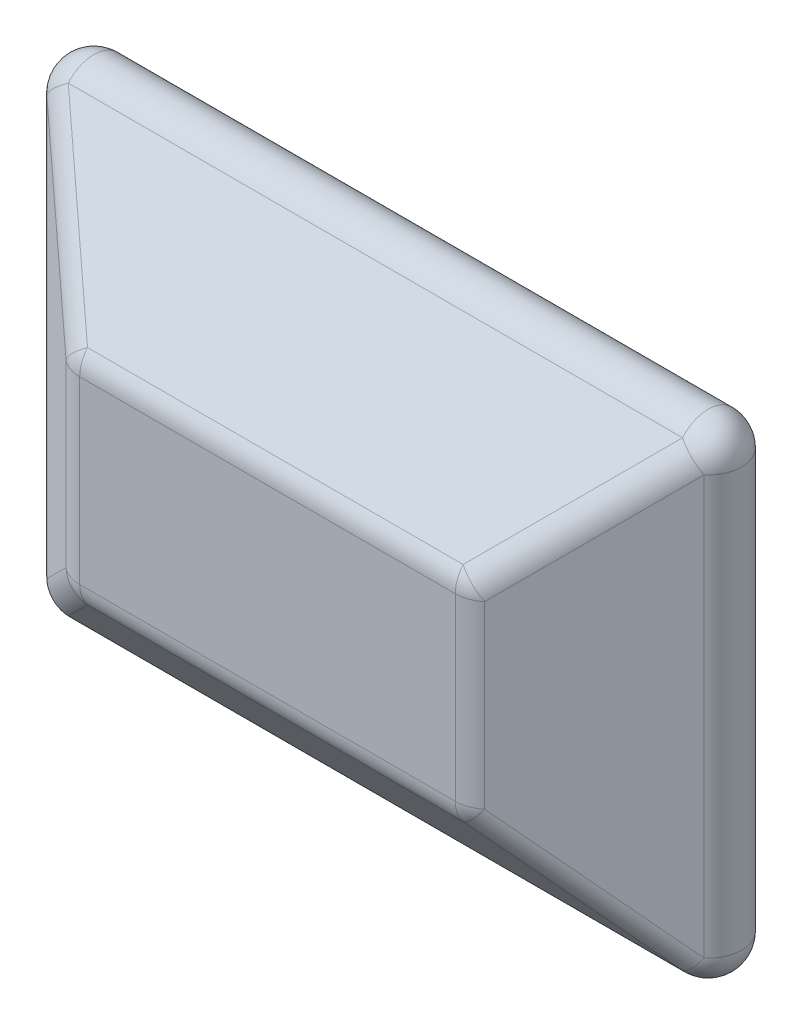
SolidWorks part; units mm, degrees
ref_plane "前视基准面" through (0, 0, 0) normal (0, 0, 1) x (1, 0, 0)
ref_plane "上视基准面" through (0, 0, 0) normal (0, 1, 0) x (1, 0, 0)
ref_plane "右视基准面" through (0, 0, 0) normal (1, 0, 0) x (0, 0, -1)
sketch "草图1" plane through (0, 0, 0) normal (0, 0, 1) x (1, 0, 0)
  line L5 (34.4735, -18.0385) -> (-34.4735, 18.0385) construction
  line L6 (34.4735, 18.0385) -> (-34.4735, -18.0385) construction
  line L7 (59.9098, -30.5731) -> (-59.9098, -30.5731)
  line L8 (59.9098, -30.5731) -> (59.9098, 30.5731)
  line L9 (59.9098, 30.5731) -> (-59.9098, 30.5731)
  line L10 (-59.9098, -30.5731) -> (-59.9098, 30.5731)
  line L11 (59.9098, -30.5731) -> (-59.9098, 30.5731) construction
  line L12 (59.9098, 30.5731) -> (-59.9098, -30.5731) construction
  point P0 (0, 0)
  point P6 (0, 0)
extrude "凸台-拉伸1" add sketch "草图1" along normal blind 50
draft "拔模8" type of draft neutral plane draft angle 50 faces to draft 4 face at (-59.9098, 0, 25) face at (0, -30.5731, 25) face at (59.9098, 0, 25) face at (0, 30.5731, 25) neutral plane through (0, 0, 50) neutral plane normal (0, 0, 1) parameters "D1"=50
fillet "圆角1" radius 10 12 edges at (-89.7036, -60.3669, 25) (0, -30.5731, 50) (0, -90.1607, 0) (89.7036, -60.3669, 25) (59.9098, 0, 50) (89.7036, 60.3669, 25) (119.4975, 0, 0) (0, 30.5731, 50) (0, 90.1607, 0) (-89.7036, 60.3669, 25) (-59.9098, 0, 50) (-119.4975, 0, 0)
sketch "草图2" plane through (0, 0, 0) normal (0, 0, -1) x (-1, 0, 0)
  line L1 (57.4134, 31.7213) -> (-57.4134, 31.7213)
  line L2 (57.4134, 31.7213) -> (57.4134, -31.7213)
  line L3 (57.4134, -31.7213) -> (-57.4134, -31.7213)
  line L4 (-57.4134, 31.7213) -> (-57.4134, -31.7213)
  line L5 (57.4134, 31.7213) -> (-57.4134, -31.7213) construction
  line L6 (57.4134, -31.7213) -> (-57.4134, 31.7213) construction
  point P0 (0, 0)
extrude "切除-拉伸1" cut sketch "草图2" against normal blind 34
